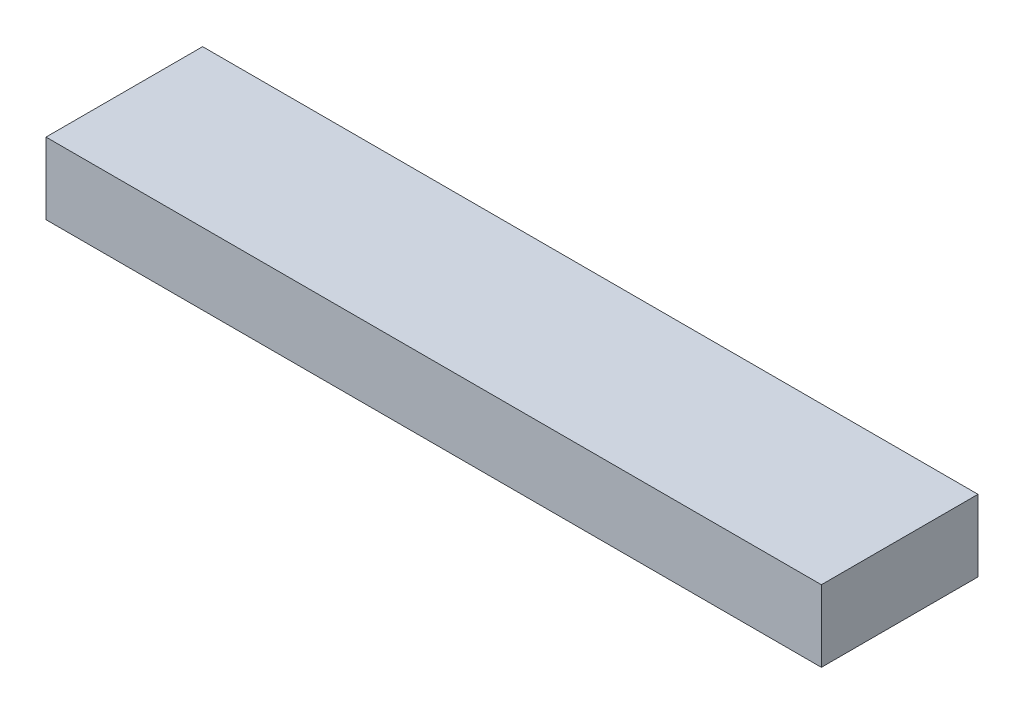
SolidWorks part; units mm, degrees
ref_plane "Front Plane" through (0, 0, 0) normal (0, 0, 1) x (1, 0, 0)
ref_plane "Top Plane" through (0, 0, 0) normal (0, 1, 0) x (1, 0, 0)
ref_plane "Right Plane" through (0, 0, 0) normal (1, 0, 0) x (0, 0, -1)
sketch "Sketch1" plane through (0, 0, 0) normal (0, 0, 1) x (1, 0, 0)
  line L1 (32.5, -3) -> (-32.5, -3)
  line L2 (32.5, -3) -> (32.5, 3)
  line L3 (32.5, 3) -> (-32.5, 3)
  line L4 (-32.5, -3) -> (-32.5, 3)
  line L5 (32.5, -3) -> (-32.5, 3) construction
  line L6 (32.5, 3) -> (-32.5, -3) construction
  point P0 (0, 0)
  dimension "D1" = 6
  dimension "D2" = 65
extrude "Boss-Extrude1" add sketch "Sketch1" along normal blind 13.1303
